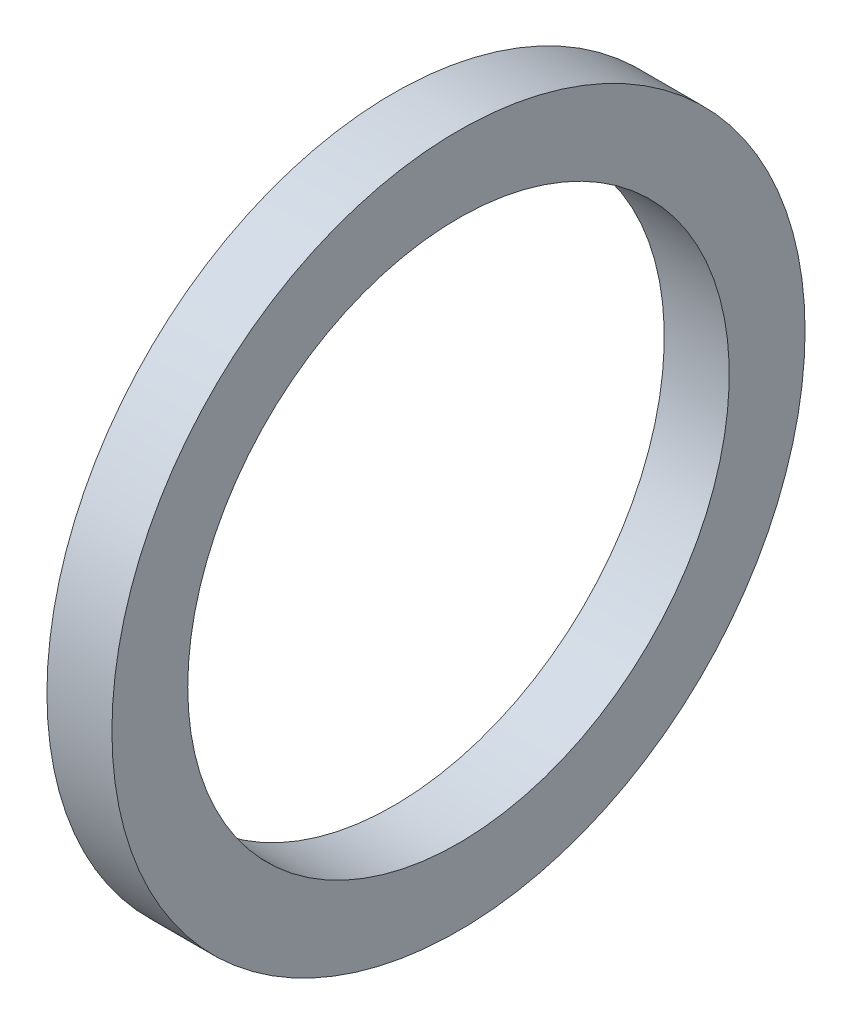
SolidWorks part; units mm, degrees
ref_plane "Plane1" through (0, 0, 0) normal (0, 0, 1) x (1, 0, 0)
ref_plane "Plane2" through (0, 0, 0) normal (0, 1, 0) x (1, 0, 0)
ref_plane "Plane3" through (0, 0, 0) normal (1, 0, 0) x (0, 0, -1)
sketch "Esquisse1" plane through (0, 0, 0) normal (0, 0, 1) x (1, 0, 0)
  line L0 (0, 0) -> (-3, 0)
  line L1 (0, 0) -> (0, 3.5)
  line L2 (-3, 3.5) -> (0, 3.5)
  line L3 (-3, 3.5) -> (-3, 0)
  dimension "D1" = 3.5
  dimension "D2" = 3
sketch "Esquisse3" plane through (0, 0, 0) normal (1, 0, 0) x (0, 0, -1)
  circle A0 centre (0, -12.5) radius 12.5
  dimension "D1" = 25
sweep "joint" add profiles "Esquisse1" path "Esquisse3"
